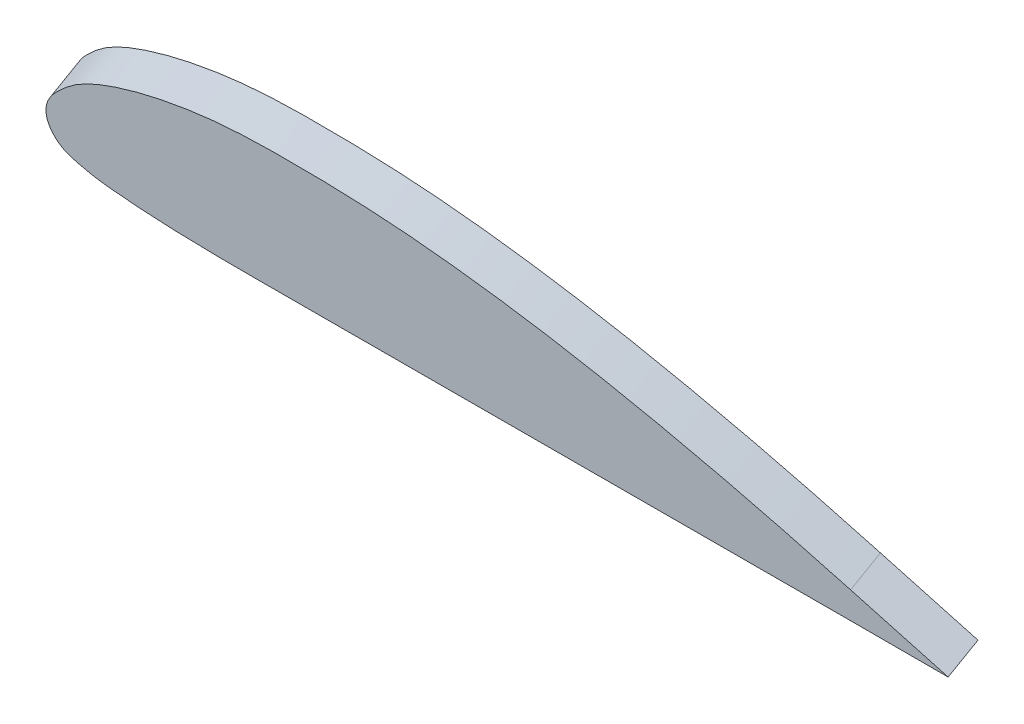
SolidWorks part; units mm, degrees
ref_plane "Front Plane" through (0, 0, 0) normal (0, 0, 1) x (1, 0, 0)
ref_plane "Top Plane" through (0, 0, 0) normal (0, 1, 0) x (1, 0, 0)
ref_plane "Right Plane" through (0, 0, 0) normal (1, 0, 0) x (0, 0, -1)
sketch "Sketch1" plane through (0, 0, 0) normal (0, 0, 1) x (1, 0, 0)
  line L4 (439.5711, 23.1125) -> (450.336, 23.1125)
  line L5 (450.336, 23.1125) -> (439.9436, 25.9631)
  spline S2 degree 3 poles (439.9436, 25.9631) (436.4828, 26.9125) (429.5501, 28.7613) (419.0411, 31.1759) (408.4537, 33.2394) (399.5297, 34.5106) (392.3512, 35.2135) (386.9325, 35.5373) (381.5275, 35.6454) (377.0153, 35.6303) (373.3666, 35.439) (370.6231, 35.1625) (367.9054, 34.7503) (365.2024, 34.2105) (362.9627, 33.6161) (361.1993, 33.0534) (359.8684, 32.5659) (358.7603, 32.0735) (357.8838, 31.6072) (357.2271, 31.203) (356.5956, 30.7475) (356.006, 30.243) (355.5007, 29.7754) (355.011, 29.2815) (354.6091, 28.7267) (354.3741, 28.2693) (354.2352, 27.7671) (354.2007, 27.3239) (354.2441, 26.9127) (354.367, 26.5021) (354.5094, 26.204) (354.7295, 25.8427) (355.0299, 25.4851) (355.4038, 25.1437) (355.8223, 24.8431) (356.2772, 24.6026) (356.8508, 24.3746) (357.5078, 24.201) (358.1444, 24.0531) (358.8514, 23.896) (359.5616, 23.7683) (360.5068, 23.6317) (361.6614, 23.5146) (363.0032, 23.4001) (364.8175, 23.2635) (367.0762, 23.1439) (369.784, 23.0556) (372.4847, 23.0108) (375.1794, 22.9945) (377.8691, 22.9964) (381.4469, 23.0094) (385.9143, 23.0177) (391.2816, 23.0244) (396.6469, 23.035) (402.0124, 23.0448) (409.1664, 23.058) (418.1088, 23.0736) (428.8398, 23.0933) (435.994, 23.1056) (439.5711, 23.1125) knots 0 0 0 0 0.0625 0.124999 0.187499 0.249998 0.281248 0.312498 0.343747 0.374997 0.390622 0.406247 0.421872 0.437497 0.453121 0.460934 0.468746 0.476559 0.480465 0.484371 0.488277 0.492184 0.49609 0.499996 0.501949 0.503902 0.504879 0.505855 0.506832 0.507809 0.508785 0.509762 0.511715 0.513668 0.515621 0.517574 0.519527 0.523433 0.52734 0.531246 0.535152 0.539058 0.546871 0.554683 0.562496 0.578121 0.593745 0.60937 0.624995 0.64062 0.656245 0.687495 0.718744 0.749994 0.781244 0.812494 0.874993 0.937493 0.999992 0.999992 0.999992 0.999992
sketch "Sketch2" plane through (0, 30, -600) normal (0, 1, 0) x (0, 0, -1)
  line L0 (-600, -397.0786) -> (-605, -398.8984)
  line L2 (-600, -354.2136) -> (-600, -439.9436) construction
  line L3 (-33.623, -148.0692) -> (-600, -354.2136) construction
  dimension "D1" = 5
sweep "Sweep1" add profiles "Sketch1" path "Sketch2"
